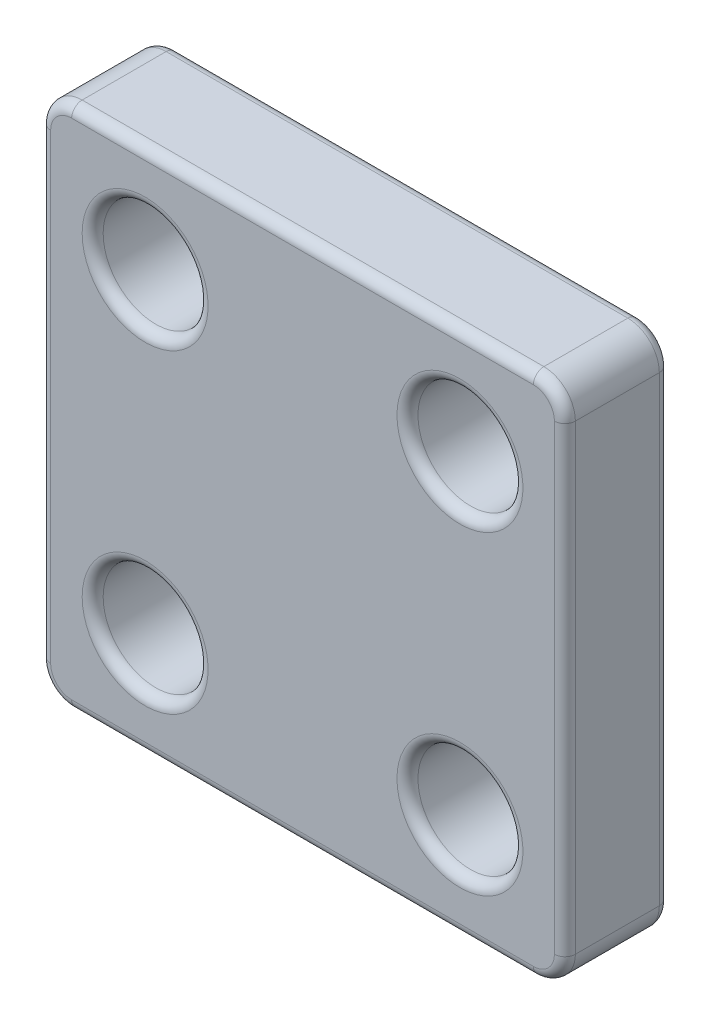
SolidWorks part; units mm, degrees
ref_plane "Front Plane" through (0, 0, 0) normal (0, 0, 1) x (1, 0, 0)
ref_plane "Top Plane" through (0, 0, 0) normal (0, 1, 0) x (1, 0, 0)
ref_plane "Right Plane" through (0, 0, 0) normal (1, 0, 0) x (0, 0, -1)
sketch "Sketch1" plane through (0, 0, 0) normal (0, 0, 1) x (1, 0, 0)
  line L1 (25, 25) -> (-25, 25)
  line L2 (25, 25) -> (25, -25)
  line L3 (25, -25) -> (-25, -25)
  line L4 (-25, 25) -> (-25, -25)
  line L5 (25, 25) -> (-25, -25) construction
  line L6 (25, -25) -> (-25, 25) construction
  point P0 (0, 0)
  dimension "D1" = 50
  dimension "D2" = 50
extrude "Boss-Extrude1" add sketch "Sketch1" along normal blind 10
sketch "Sketch2" plane through (0, 0, 10) normal (0, 0, 1) x (1, 0, 0)
  line L1 (15, 15) -> (-15, 15) construction
  line L2 (15, 15) -> (15, -15) construction
  line L3 (15, -15) -> (-15, -15) construction
  line L4 (-15, 15) -> (-15, -15) construction
  line L5 (15, 15) -> (-15, -15) construction
  line L6 (15, -15) -> (-15, 15) construction
  circle A0 centre (-15, 15) radius 5
  circle A1 centre (15, 15) radius 5
  circle A2 centre (15, -15) radius 5
  circle A3 centre (-15, -15) radius 5
  point P0 (0, 0)
  point P6 (0, 15)
  dimension "D3" = 10
  dimension "D4" = 10
  dimension "D5" = 10
  dimension "D6" = 10
  dimension "D1" = 30
  dimension "D2" = 30
extrude "Cut-Extrude1" cut sketch "Sketch2" against normal blind 10 contours A1 | A2 | A3 | A0
fillet "Fillet1" radius 3 4 edges at (-25, 25, 5) (-25, -25, 5) (25, -25, 5) (25, 25, 5)
fillet "Fillet2" radius 1 24 edges at (24.1213, 24.1213, 0) (25, 0, 0) (24.1213, -24.1213, 0) (0, -25, 0) (-24.1213, -24.1213, 0) (-25, 0, 0) (-24.1213, 24.1213, 0) (24.1213, 24.1213, 10) (25, 0, 10) (24.1213, -24.1213, 10) (0, -25, 10) (-24.1213, -24.1213, 10) (-25, 0, 10) (-24.1213, 24.1213, 10) (20, -15, 0) (20, -15, 10) (-10, -15, 0) (-10, -15, 10) (-10, 15, 10) (-10, 15, 0) (20, 15, 10) (20, 15, 0) (0, 25, 0) (0, 25, 10)
